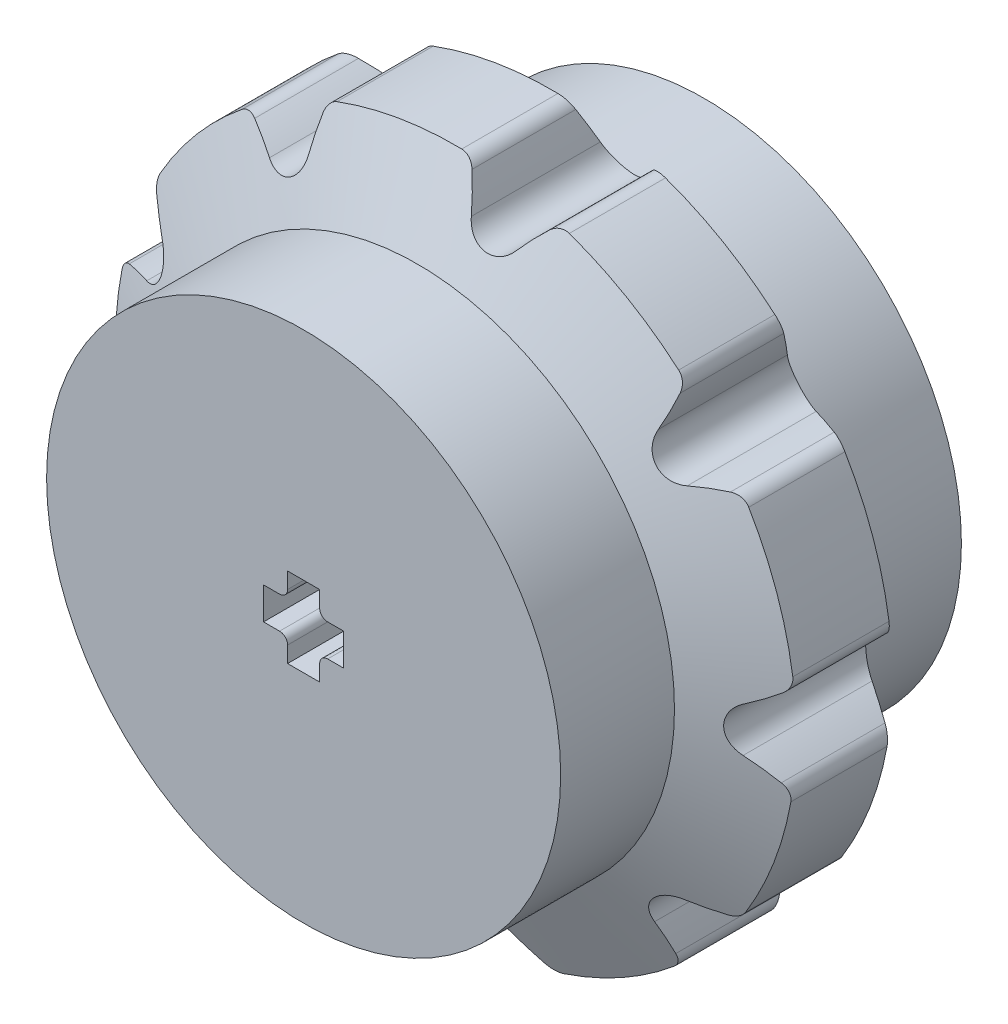
SolidWorks part; units mm, degrees
material "ABS"
ref_plane "Front" through (0, 0, 0) normal (0, 0, 1) x (1, 0, 0)
ref_plane "Top" through (0, 0, 0) normal (0, 1, 0) x (1, 0, 0)
ref_plane "Right" through (0, 0, 0) normal (1, 0, 0) x (0, 0, -1)
ref_axis "Axis1" through (0, 0, -80.9) along (0, 0, 1)
sketch "Sketch2" plane through (0, 0, 0) normal (0, 0, 1) x (1, 0, 0)
  line L0 (12.7692, 11.8308) -> (17.3864, -0.8551)
  line L1 (-9.8678, 17.0916) -> (-18.5455, 6.75) construction
  line L2 (-18.5455, 6.75) -> (-18.5455, -6.75) construction
  line L3 (-18.5455, -6.75) -> (-9.8678, -17.0916) construction
  line L4 (-9.8678, -17.0916) -> (3.4271, -19.4359) construction
  line L5 (3.4271, -19.4359) -> (15.1184, -12.6859) construction
  line L6 (15.1184, -12.6859) -> (19.7357, 0) construction
  line L7 (19.7357, 0) -> (15.1184, 12.6859) construction
  line L8 (15.1184, 12.6859) -> (3.4271, 19.4359) construction
  line L9 (3.4271, 19.4359) -> (-9.8678, 17.0916) construction
  line L10 (15.1184, 12.6859) -> (17.9375, 13.7119)
  line L11 (17.9375, 13.7119) -> (22.5548, 1.0261)
  line L12 (22.5548, 1.0261) -> (19.7357, 0)
  circle A0 centre (0, 0) radius 18.5455 construction
  circle A1 centre (0, 0) radius 19.7357 construction
  circle A2 centre (15.1184, 12.6859) radius 2.5
  circle A3 centre (19.7357, 0) radius 2.5
  dimension "D2" = 39.4714
  dimension "D4" = 3
  dimension "D1" = 13.5
  dimension "D3" = 2.5
sketch "Sketch1" plane through (0, 0, 0) normal (0, 1, 0) x (1, 0, 0)
  line L0 (0, 0) -> (0, -50000) construction
  line L1 (3, 12.5) -> (16.0357, 12.5)
  line L2 (16.0357, 12.5) -> (16.0357, 5.4)
  line L3 (16.0357, 5.4) -> (21.2357, 3)
  line L4 (21.2357, 3) -> (21.2357, -3)
  line L5 (21.2357, -3) -> (16.0357, -5.4)
  line L6 (16.0357, -5.4) -> (16.0357, -12.5)
  line L7 (16.0357, -12.5) -> (12.0357, -12.5)
  line L8 (12.0357, -12.5) -> (10, -2.5)
  line L9 (10, -2.5) -> (3, -2.5)
  line L10 (3, -2.5) -> (3, 12.5)
  line L11 (21.2357, 0) -> (0, 0) construction
  line L12 (19.7357, 3.6923) -> (19.7357, -3.6923) construction
  point P19 (19.7357, 0)
  dimension "D1" = 6
  dimension "D2" = 10.8
  dimension "D3" = 25
  dimension "D4" = 3.7
  dimension "D5" = 6
  dimension "D6" = 20
  dimension "D7" = 4
  dimension "D8" = 15
  dimension "D9" = 1.5
  dimension "D10" = 42.4714
  dimension "D11" = 32.0714
revolve "Revolve1" add sketch "Sketch1" angle 360 about L0
sketch "Sketch3" plane through (0, 0, 12.5) normal (0, 0, 1) x (1, 0, 0)
  line L0 (0, 0) -> (21.2357, 0) construction
  circle A0 centre (19.7357, 0) radius 1.6 construction
  circle A1 centre (0, 0) radius 19.7357 construction
  arc A2 (20.9606, 3.4072) -> (20.9606, -3.4072) centre (0, 0) cw
  circle A3 centre (0, 0) radius 21.2357 construction
  arc A4 (18.9656, 1.4025) -> (18.9656, -1.4025) centre (19.7357, 0) ccw
  arc A5 (20.9606, 3.4072) -> (20.5789, 2.4508) centre (19.9735, 3.2467) cw
  arc A6 (20.5789, 2.4508) -> (18.9656, 1.4025) centre (12.7085, 12.7976) cw
  arc A7 (20.5789, -2.4508) -> (18.9656, -1.4025) centre (12.7085, -12.7976) ccw
  arc A8 (20.9606, -3.4072) -> (20.5789, -2.4508) centre (19.9735, -3.2467) ccw
  circle A9 centre (0, 0) radius 18.0357 construction
  circle A10 centre (0, 0) radius 16.0357 construction
  dimension "D1" = 3.2
  dimension "D3" = 1
  dimension "D4" = 13
  dimension "D2" = 2
extrude "Cut-Extrude1" cut sketch "Sketch3" against normal through all
sketch "Sketch4" plane through (0, 0, 12.5) normal (0, 0, 1) x (1, 0, 0)
  line L0 (0, -16.0357) -> (0, 22.3368)
  line L1 (0, -16.0357) -> (0, -23.3005)
  circle A0 centre (0, 0) radius 16.0357 construction
  circle A1 centre (0, 0) radius 16.0357 construction
sketch "Sketch5" plane through (0, 0, 0) normal (1, 0, 0) x (0, 0, -1)
  line L0 (-12.5, 22.251) -> (13.794, 22.251)
  line L1 (-12.5, -16.0357) -> (-12.5, 22.3368) construction
  line L2 (13.794, 22.251) -> (13.794, -22.7901)
  line L3 (13.794, -22.7901) -> (-12.5, -23.3005)
  line L4 (-12.5, -16.0357) -> (-12.5, -23.3005) construction
ref_plane "Plane1" through (0, 0, 0) normal (-1, 0, 0) x (0, 0, 1)
sketch "Sketch6" plane through (0, 0, 0) normal (-1, 0, 0) x (0, 0, 1)
  line L1 (12.5, -16.0357) -> (12.5, 22.3368) construction
  line L2 (12.5, 3) -> (12.5, 12.0357)
  line L4 (12.5, -3) -> (12.5, -12.0357)
  line L7 (-12.5, 0) -> (12.5, 0)
  line L8 (-12.5, -3) -> (12.5, -3)
  line L9 (-12.5, 3) -> (12.5, 3)
  line L20 (3, 21.2357) -> (-3, 21.2357)
  line L21 (-5.4, 16.0357) -> (-12.5, 16.0357)
  line L22 (-3, 21.2357) -> (-5.4, 16.0357)
  line L23 (5.4, 16.0357) -> (3, 21.2357)
  line L24 (12.5, 16.0357) -> (5.4, 16.0357)
  line L25 (12.5, 12.0357) -> (12.5, 16.0357)
  line L29 (-12.5, 16.0357) -> (-12.5, 3)
  line L30 (-12.5, -3) -> (-12.5, -16.0357)
  line L34 (12.5, -16.0357) -> (12.5, -12.0357)
  line L35 (5.4, -16.0357) -> (12.5, -16.0357)
  line L36 (3, -21.2357) -> (5.4, -16.0357)
  line L37 (-5.4, -16.0357) -> (-3, -21.2357)
  line L38 (-12.5, -16.0357) -> (-5.4, -16.0357)
  line L39 (-3, -21.2357) -> (3, -21.2357)
revolve "Revolve5" add sketch "Sketch6" angle 360 about L7
pattern_circular "CirPattern1" count 10 over 359 about axis through (0, 0, -80.9) along (0, 0, 1) of "Cut-Extrude1"
sketch "Sketch7" plane through (0, 0, -12.5) normal (0, 0, -1) x (-1, 0, 0)
  line L1 (2.5, 0) -> (2.5, -1)
  line L2 (2.5, -1) -> (1.5, -1)
  line L4 (2.5, 1) -> (1.5, 1)
  line L5 (2.5, 0) -> (2.5, 1)
  line L6 (1, -2.5) -> (1, -1.5)
  line L7 (0, -2.5) -> (1, -2.5)
  line L8 (0, -2.5) -> (-1, -2.5)
  line L9 (-1, -2.5) -> (-1, -1.5)
  line L10 (-2.5, -1) -> (-1.5, -1)
  line L11 (-2.5, 0) -> (-2.5, -1)
  line L12 (-2.5, 0) -> (-2.5, 1)
  line L13 (-2.5, 1) -> (-1.5, 1)
  line L14 (-1, 2.5) -> (-1, 1.5)
  line L15 (0, 2.5) -> (-1, 2.5)
  line L16 (0, 2.5) -> (1, 2.5)
  line L17 (1, 2.5) -> (1, 1.5)
  circle A0 centre (0, 0) radius 3
  arc A1 (-1, -1.5) -> (-1.5, -1) centre (-1.5, -1.5) ccw
  arc A2 (1, -1.5) -> (1.5, -1) centre (1.5, -1.5) cw
  arc A3 (1.5, 1) -> (1, 1.5) centre (1.5, 1.5) cw
  arc A4 (-1.5, 1) -> (-1, 1.5) centre (-1.5, 1.5) ccw
  point P21 (1, 1)
  point P28 (0, 0)
  dimension "D7" = 0.5
  dimension "D1" = 1
  dimension "D2" = 2.5
  dimension "D3" = 4
  dimension "D4" = 1.5
  dimension "D5" = 1
  dimension "D6" = 1.5
extrude "Boss-Extrude1" add sketch "Sketch7" against normal blind 25
